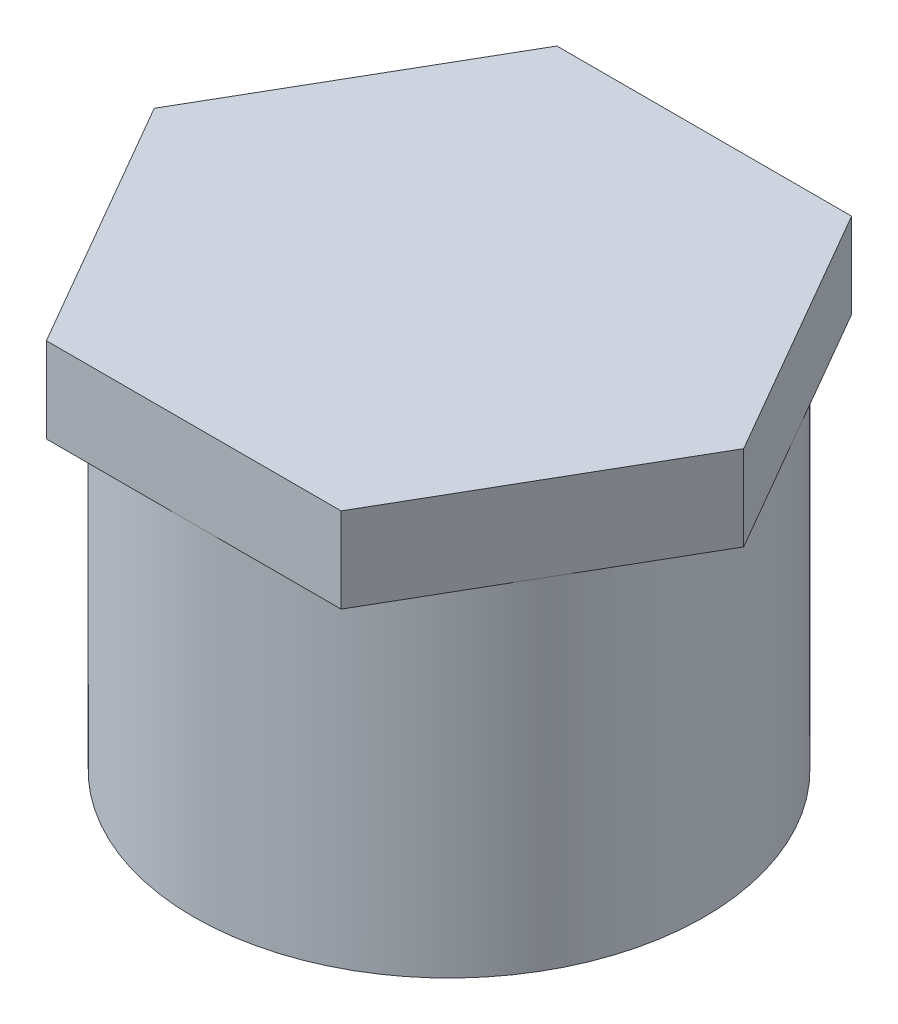
SolidWorks part; units mm, degrees
ref_plane "Front Plane" through (0, 0, 0) normal (0, 0, 1) x (1, 0, 0)
ref_plane "Top Plane" through (0, 0, 0) normal (0, 1, 0) x (1, 0, 0)
ref_plane "Right Plane" through (0, 0, 0) normal (1, 0, 0) x (0, 0, -1)
sketch "Sketch1" plane through (0, 0, 0) normal (0, 1, 0) x (1, 0, 0)
  circle A0 centre (0, 0) radius 3.81
  dimension "D1" = 7.62
extrude "Boss-Extrude1" add sketch "Sketch1" along normal blind 5.08
cosmetic thread "Cosmetic Thread1" parameters "D2"=5.268
sketch "Sketch2" plane through (0, 5.08, 0) normal (0, 1, 0) x (1, 0, 0)
  line L0 (-2.1997, 3.81) -> (2.1997, 3.81)
  line L1 (2.1997, 3.81) -> (4.3994, 0)
  line L2 (4.3994, 0) -> (2.1997, -3.81)
  line L3 (2.1997, -3.81) -> (-2.1997, -3.81)
  line L4 (-2.1997, -3.81) -> (-4.3994, 0)
  line L5 (-4.3994, 0) -> (-2.1997, 3.81)
  line L6 (-2.1997, 3.81) -> (-2.1997, -3.81) construction
  line L7 (2.1997, -3.81) -> (2.1997, 3.81) construction
  line L8 (4.3994, 0) -> (-4.3994, 0) construction
  circle A0 centre (0, 0) radius 3.81 construction
extrude "Boss-Extrude2" add sketch "Sketch2" along normal blind 1.27
